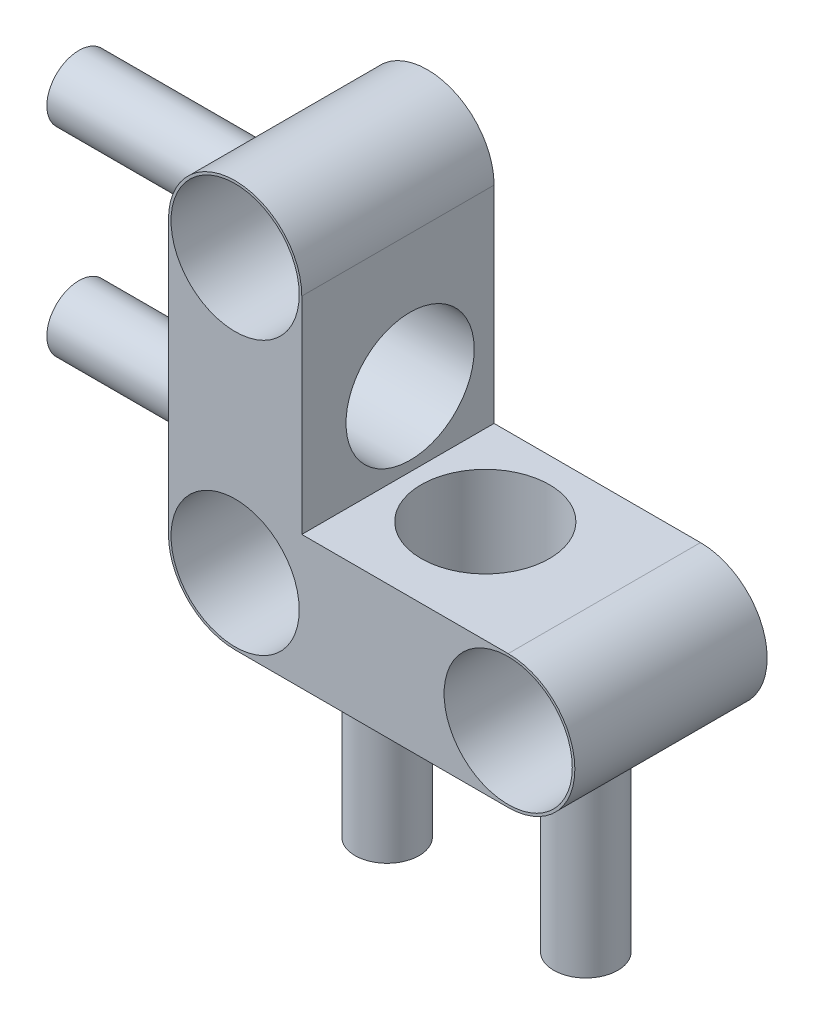
SolidWorks part; units mm, degrees
ref_plane "Front Plane" through (0, 0, 0) normal (0, 0, 1) x (1, 0, 0)
ref_plane "Top Plane" through (0, 0, 0) normal (0, 1, 0) x (1, 0, 0)
ref_plane "Right Plane" through (0, 0, 0) normal (1, 0, 0) x (0, 0, -1)
sketch "Sketch1" plane through (0, 0, 0) normal (0, 0, 1) x (1, 0, 0)
  line L0 (-0.52, 2.13) -> (-0.52, 0)
  line L1 (0, -0.52) -> (2.13, -0.52)
  line L2 (0.52, 2.13) -> (0.52, 0.52)
  line L3 (0.52, 0.52) -> (2.13, 0.52)
  circle A0 centre (0, 0) radius 0.52
  circle A1 centre (0, 0) radius 0.5
  circle A2 centre (0, 2.13) radius 0.5
  circle A3 centre (0, 2.13) radius 0.52
  circle A4 centre (2.13, 0) radius 0.5
  circle A5 centre (2.13, 0) radius 0.52
  dimension "D1" = 2
  dimension "D2" = 2
extrude "Boss-Extrude1" add sketch "Sketch1" along normal blind 1.5 contours A5 L3 L2 A3 L0 A0 L1 | A3 A2 | A0 A1 | A5 A4
sketch "Sketch2" plane through (0.52, 0, 0) normal (1, 0, 0) x (0, 0, -1)
  circle A0 centre (-0.655, 1.0988) radius 0.5
sketch "Sketch3" plane through (0, 0, 0) normal (0, 1, 0) x (1, 0, 0)
  circle A0 centre (1.1493, -0.6977) radius 0.5
extrude "Cut-Extrude12" cut sketch "Sketch2" against normal blind 2
extrude "Cut-Extrude14" cut sketch "Sketch3" against normal blind 2 and the other way blind 4
sketch "Sketch5" plane through (-0.52, 0, 0) normal (-1, 0, 0) x (0, 0, 1)
  circle A0 centre (0.6986, 1.8694) radius 0.25
  circle A1 centre (0.6986, 0.314) radius 0.25
extrude "Boss-Extrude2" add sketch "Sketch5" along normal blind 1.5
sketch "Sketch6" plane through (0, -0.52, 0) normal (0, -1, 0) x (1, 0, 0)
  circle A0 centre (1.9077, 0.6723) radius 0.25
  circle A1 centre (0.3577, 0.6723) radius 0.25
  dimension "D1" = 0.5
  dimension "D2" = 0.5
extrude "Boss-Extrude3" add sketch "Sketch6" along normal blind 1.5
